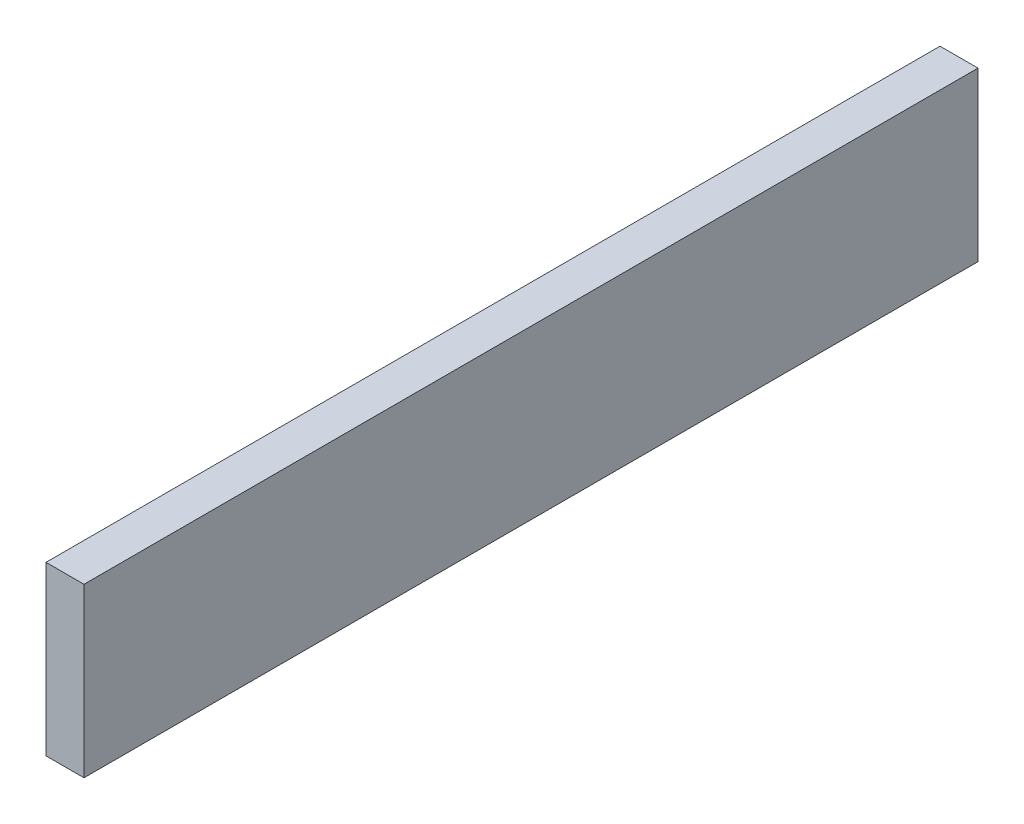
SolidWorks part; units mm, degrees
ref_plane "Front Plane" through (0, 0, 0) normal (0, 0, 1) x (1, 0, 0)
ref_plane "Top Plane" through (0, 0, 0) normal (0, 1, 0) x (1, 0, 0)
ref_plane "Right Plane" through (0, 0, 0) normal (1, 0, 0) x (0, 0, -1)
sketch "Sketch1" plane through (0, 0, 0) normal (0, 1, 0) x (1, 0, 0)
  line L1 (0, 0) -> (3.4, 0)
  line L2 (0, 0) -> (0, 80)
  line L3 (0, 80) -> (3.4, 80)
  line L4 (3.4, 0) -> (3.4, 80)
  dimension "D1" = 3.4
  dimension "D2" = 80
extrude "Boss-Extrude1" add sketch "Sketch1" along normal blind 15
